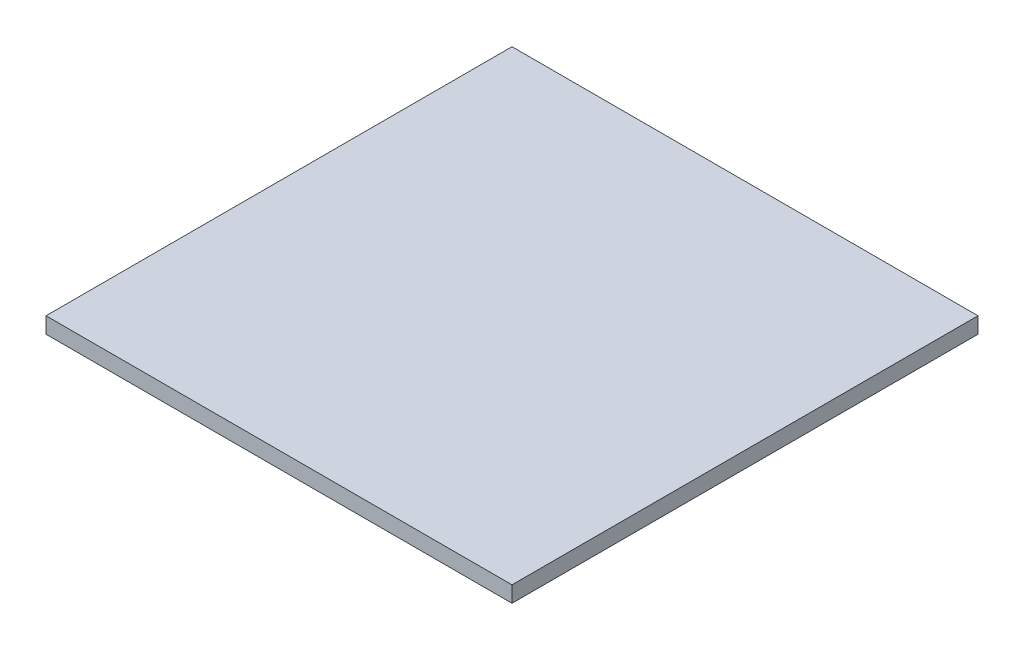
SolidWorks part; units mm, degrees
ref_plane "Front Plane" through (0, 0, 0) normal (0, 0, 1) x (1, 0, 0)
ref_plane "Top Plane" through (0, 0, 0) normal (0, 1, 0) x (1, 0, 0)
ref_plane "Right Plane" through (0, 0, 0) normal (1, 0, 0) x (0, 0, -1)
sketch "Sketch1" plane through (0, 0, 0) normal (0, 1, 0) x (1, 0, 0)
  line L0 (-88.9, -153.9875) -> (88.9, -153.9875) construction
  line L1 (254, -254) -> (-254, -254)
  line L2 (254, -254) -> (254, 254)
  line L3 (254, 254) -> (-254, 254)
  line L4 (-254, -254) -> (-254, 254)
  line L5 (254, -254) -> (-254, 254) construction
  line L6 (254, 254) -> (-254, -254) construction
  line L7 (0, -153.9875) -> (0, 0) construction
  circle A0 centre (-88.9, -153.9875) radius 31.75
  circle A1 centre (88.9, -153.9875) radius 31.75
  point P0 (0, 0)
  dimension "D7" = 63.5
  dimension "D1" = 508
  dimension "D2" = 508
  dimension "D3" = 177.8
  dimension "D4" = 100.0125
extrude "Boss-Extrude1" add sketch "Sketch1" along normal blind 17.4625 contours A0 | A1 | L4 L1 L2 L3 A1 A0
